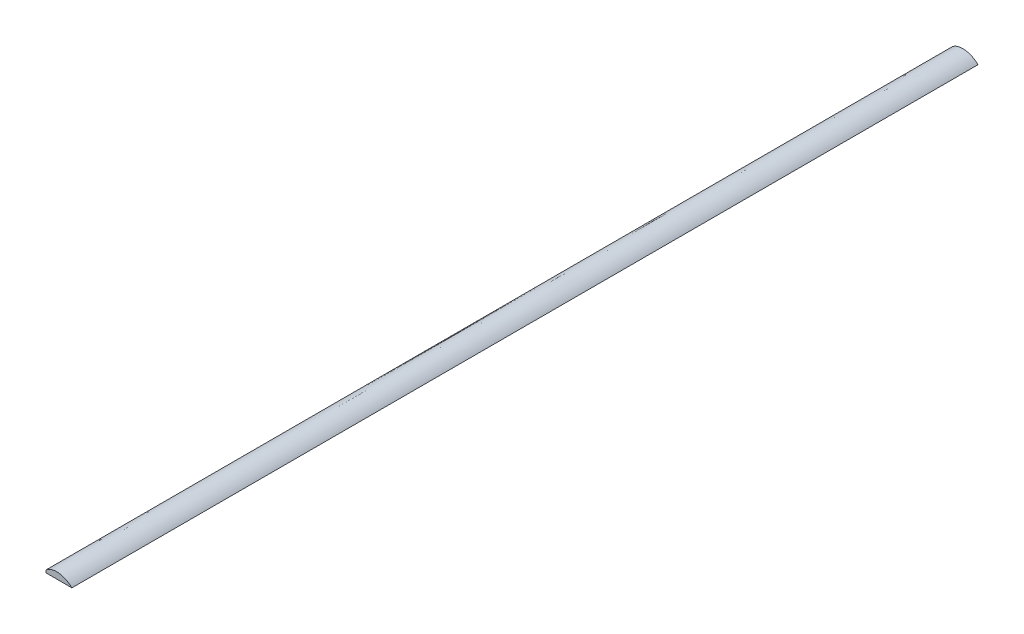
SolidWorks part; units mm, degrees
ref_plane "Front Plane" through (0, 0, 0) normal (0, 0, 1) x (1, 0, 0)
ref_plane "Top Plane" through (0, 0, 0) normal (0, 1, 0) x (1, 0, 0)
ref_plane "Right Plane" through (0, 0, 0) normal (1, 0, 0) x (0, 0, -1)
sketch "Sketch1" plane through (0, 0, 0) normal (0, 0, 1) x (1, 0, 0)
  line L0 (0, 0) -> (2, 0)
  line L1 (0, 0) -> (0, 0.2)
  spline S0 degree 3 poles (0, 0.2) (0.5607, 0.701) (1.5092, 0.5071) (2, 0) knots 0 0 0 0 1 1 1 1
  dimension "D1" = 2
  dimension "D2" = 0.2
extrude "Boss-Extrude1" add sketch "Sketch1" against normal blind 70
